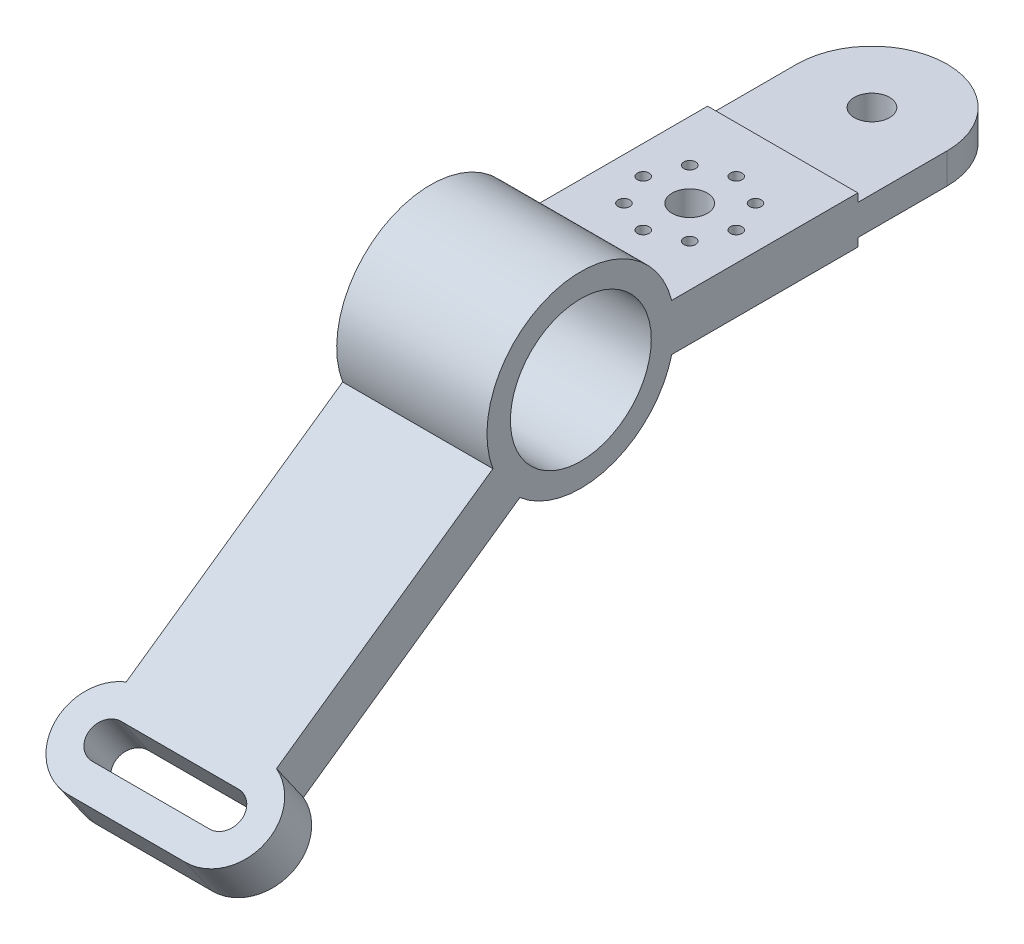
SolidWorks part; units mm, degrees
material "___"
ref_plane "Front Plane" through (0, 0, 0) normal (0, 0, 1) x (1, 0, 0)
ref_plane "Top Plane" through (0, 0, 0) normal (0, 1, 0) x (1, 0, 0)
ref_plane "Right Plane" through (0, 0, 0) normal (1, 0, 0) x (0, 0, -1)
sketch "Sketch1" plane through (0, 0, 0) normal (1, 0, 0) x (0, 0, -1)
  line L0 (0, 0) -> (11.4715, -16.383)
  line L1 (11.4715, -16.383) -> (119.0018, 58.9104)
  line L2 (0, 0) -> (107.5302, 75.2935)
  line L3 (107.5302, 75.2935) -> (13.8289, 75.2935) construction
  line L4 (144.9916, 89.3165) -> (396.8204, 89.3165) construction
  line L5 (262.9916, 99.3165) -> (183.7214, 99.3165)
  line L6 (262.9916, 99.3165) -> (262.9916, 95.8165)
  line L7 (262.9916, 79.3165) -> (183.7214, 79.3165)
  line L8 (262.9916, 95.8165) -> (300.9916, 95.8165)
  line L9 (300.9916, 95.8165) -> (300.9916, 82.8165)
  line L10 (300.9916, 82.8165) -> (262.9916, 82.8165)
  line L11 (262.9916, 82.8165) -> (262.9916, 79.3165)
  arc A0 (119.0018, 58.9104) -> (183.7214, 79.3165) centre (144.9916, 89.3165) ccw
  arc A1 (183.7214, 99.3165) -> (107.5302, 75.2935) centre (144.9916, 89.3165) ccw
  circle A2 centre (144.9916, 89.3165) radius 30
  point P15 (300.9916, 89.3165)
  dimension "D3" = 80
  dimension "D9" = 60
  dimension "D1" = 35
  dimension "D2" = 20
  dimension "D4" = 170
  dimension "D5" = 20
  dimension "D6" = 118
  dimension "D7" = 156
  dimension "D8" = 13
  dimension "D10" = 3.5
extrude "Boss-Extrude1" add sketch "Sketch1" along normal mid plane 64
sketch "Sketch2" plane through (0, 0, 0) normal (0, 0.8192, 0.5736) x (1, 0, 0)
  line L0 (25, 0) -> (-25, 0) construction
  line L1 (32, 0) -> (-32, 0) construction
  line L2 (25, -20) -> (-25, -20)
  line L3 (25, 20) -> (-25, 20)
  arc A0 (25, -20) -> (25, 20) centre (25, 0) ccw
  arc A1 (-25, 20) -> (-25, -20) centre (-25, 0) ccw
  point P5 (0, 0)
  dimension "D2" = 20
  dimension "D1" = 50
extrude "Cut-Extrude1" cut sketch "Sketch2" against normal blind 64
sketch "Sketch3" plane through (0, 0, 0) normal (0, 0.8192, 0.5736) x (1, 0, 0)
  line L0 (25, 0) -> (-25, 0) construction
  line L1 (25, -20) -> (-25, -20)
  line L2 (25, 20) -> (-25, 20)
  line L3 (25, 20) -> (-25, 20) construction
  line L4 (25, 0) -> (-25, 0) construction
  line L5 (25, -7.5) -> (-25, -7.5)
  line L6 (25, 7.5) -> (-25, 7.5)
  arc A0 (25, -20) -> (25, 20) centre (25, 0) ccw
  arc A1 (-25, 20) -> (-25, -20) centre (-25, 0) ccw
  arc A2 (25, -7.5) -> (25, 7.5) centre (25, 0) ccw
  arc A3 (-25, 7.5) -> (-25, -7.5) centre (-25, 0) ccw
  point P2 (0, 0)
  point P12 (0, 0)
  dimension "D2" = 20
  dimension "D1" = 50
  dimension "D3" = 15
extrude "Boss-Extrude2" add sketch "Sketch3" against normal up to surface (20 mm away) up to face at (0, 16.1806, -57.9772)
sketch "Sketch4" plane through (0, 99.3165, 0) normal (0, 1, 0) x (1, 0, 0)
  line L1 (0, 223.3714) -> (0, 262.9916) construction
  line L2 (32, 262.9916) -> (-32, 262.9916) construction
  line L4 (32, 183.7214) -> (-32, 183.7214) construction
  circle A0 centre (0, 223.3714) radius 7.5
  circle A1 centre (0, 223.3714) radius 20 construction
  circle A2 centre (0, 243.1815) radius 2.5
  dimension "D1" = 15
  dimension "D3" = 40
  dimension "D4" = 5
  dimension "D2" = 39.65
extrude "Cut-Extrude2" cut sketch "Sketch4" against normal blind 64
pattern_circular "CirPattern1" count 8 over 360 about axis through (0, 0, -223.3714) along (0, 1, 0) of "Cut-Extrude2"
sketch "Sketch5" plane through (0, 95.8165, 0) normal (0, 1, 0) x (1, 0, 0)
  line L0 (32, 300.9916) -> (-32, 300.9916) construction
  line L1 (-32, 300.9916) -> (32, 300.9916)
  arc A0 (-32, 300.9916) -> (32, 300.9916) centre (0, 300.9916) cw
  point P3 (0, 0)
extrude "Boss-Extrude3" add sketch "Sketch5" against normal up to surface (13 mm away) up to face at (0, 82.8165, -281.9916)
sketch "Sketch6" plane through (0, 95.8165, 0) normal (0, 1, 0) x (1, 0, 0)
  circle A0 centre (0, 300.9916) radius 7.5
  circle A1 centre (0, 223.3714) radius 7.5 construction
  arc A2 (32, 300.9916) -> (-32, 300.9916) centre (0, 300.9916) ccw construction
  point P4 (0, 0)
  point P5 (0, 0)
extrude "Cut-Extrude3" cut sketch "Sketch6" against normal blind 64
